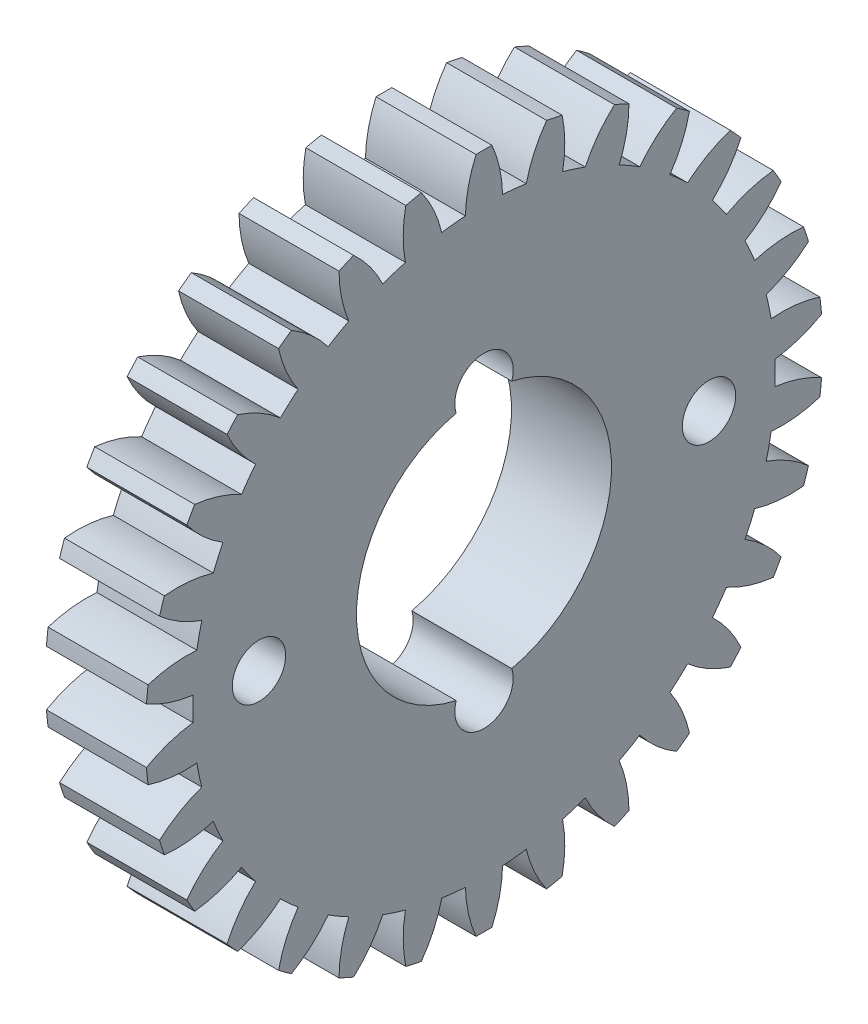
SolidWorks part; units mm, degrees
material "Aço 4140"
ref_plane "Plano frontal" through (0, 0, 0) normal (0, 0, 1) x (1, 0, 0)
ref_plane "Plano superior" through (0, 0, 0) normal (0, 1, 0) x (1, 0, 0)
ref_plane "Plano direito" through (0, 0, 0) normal (1, 0, 0) x (0, 0, -1)
ref_plane "Plano1" through (0, 0, 0) normal (-1, 0, 0) x (0, -1, 0)
sketch "Esboço1" plane through (0, 0, 0) normal (-1, 0, 0) x (0, -1, 0)
  circle A0 centre (8, 0) radius 1.75
  circle A1 centre (0, 0) radius 3
  circle A2 centre (-8, 0) radius 1.75
  arc A3 (17.4396, -1.1143) -> (20.3144, -0.4769) centre (17.2585, 6.5035) ccw
  arc A4 (20.3144, -0.4769) -> (20.3144, 0.4769) centre (0, 0) ccw
  arc A5 (20.3144, 0.4769) -> (17.4396, 1.1143) centre (17.2585, -6.5035) ccw
  arc A6 (17.4396, 1.1143) -> (17.2902, 2.5359) centre (0, 0) ccw
  arc A7 (17.2902, 2.5359) -> (19.9696, 3.7571) centre (15.5292, 9.9496) ccw
  arc A8 (19.9696, 3.7571) -> (19.7713, 4.6901) centre (0, 0) ccw
  arc A9 (19.7713, 4.6901) -> (16.8269, 4.7159) centre (18.2335, -2.7732) ccw
  arc A10 (16.8269, 4.7159) -> (16.3851, 6.0754) centre (0, 0) ccw
  arc A11 (16.3851, 6.0754) -> (18.7521, 7.827) centre (13.1212, 12.9609) ccw
  arc A12 (18.7521, 7.827) -> (18.3642, 8.6983) centre (0, 0) ccw
  arc A13 (18.3642, 8.6983) -> (15.4787, 8.1113) centre (18.4117, 1.0784) ccw
  arc A14 (15.4787, 8.1113) -> (14.7639, 9.3493) centre (0, 0) ccw
  arc A15 (14.7639, 9.3493) -> (16.715, 11.5547) centre (10.1398, 15.4058) ccw
  arc A16 (16.715, 11.5547) -> (16.1544, 12.3263) centre (0, 0) ccw
  arc A17 (16.1544, 12.3263) -> (13.454, 11.1523) centre (17.7851, 4.8828) ccw
  arc A18 (13.454, 11.1523) -> (12.4975, 12.2145) centre (0, 0) ccw
  arc A19 (12.4975, 12.2145) -> (13.9474, 14.7775) centre (6.7151, 17.1773) ccw
  arc A20 (13.9474, 14.7775) -> (13.2386, 15.4156) centre (0, 0) ccw
  arc A21 (13.2386, 15.4156) -> (10.8413, 13.7058) centre (16.3813, 8.4739) ccw
  arc A22 (10.8413, 13.7058) -> (9.6849, 14.546) centre (0, 0) ccw
  arc A23 (9.6849, 14.546) -> (10.5702, 17.3544) centre (2.997, 18.1981) ccw
  arc A24 (10.5702, 17.3544) -> (9.7442, 17.8312) centre (0, 0) ccw
  arc A25 (9.7442, 17.8312) -> (7.7548, 15.6603) centre (14.2615, 11.6946) ccw
  arc A26 (7.7548, 15.6603) -> (6.4489, 16.2417) centre (0, 0) ccw
  arc A27 (6.4489, 16.2417) -> (6.731, 19.1728) centre (-0.852, 18.4235) ccw
  arc A28 (6.731, 19.1728) -> (5.824, 19.4675) centre (0, 0) ccw
  arc A29 (5.824, 19.4675) -> (4.3294, 16.9304) centre (11.5184, 14.4041) ccw
  arc A30 (4.3294, 16.9304) -> (2.9312, 17.2276) centre (0, 0) ccw
  arc A31 (2.9312, 17.2276) -> (2.5977, 20.1533) centre (-4.6639, 17.8438) ccw
  arc A32 (2.5977, 20.1533) -> (1.6492, 20.253) centre (0, 0) ccw
  arc A33 (1.6492, 20.253) -> (0.7147, 17.4606) centre (8.2719, 16.4842) ccw
  arc A34 (0.7147, 17.4606) -> (-0.7147, 17.4606) centre (0, 0) ccw
  arc A35 (-0.7147, 17.4606) -> (-1.6492, 20.253) centre (-8.2719, 16.4842) ccw
  arc A36 (-1.6492, 20.253) -> (-2.5977, 20.1533) centre (0, 0) ccw
  arc A37 (-2.5977, 20.1533) -> (-2.9312, 17.2276) centre (4.6639, 17.8438) ccw
  arc A38 (-2.9312, 17.2276) -> (-4.3294, 16.9304) centre (0, 0) ccw
  arc A39 (-4.3294, 16.9304) -> (-5.824, 19.4675) centre (-11.5184, 14.4041) ccw
  arc A40 (-5.824, 19.4675) -> (-6.731, 19.1728) centre (0, 0) ccw
  arc A41 (-6.731, 19.1728) -> (-6.4489, 16.2417) centre (0.852, 18.4235) ccw
  arc A42 (-6.4489, 16.2417) -> (-7.7548, 15.6603) centre (0, 0) ccw
  arc A43 (-7.7548, 15.6603) -> (-9.7442, 17.8312) centre (-14.2615, 11.6946) ccw
  arc A44 (-9.7442, 17.8312) -> (-10.5702, 17.3544) centre (0, 0) ccw
  arc A45 (-10.5702, 17.3544) -> (-9.6849, 14.546) centre (-2.997, 18.1981) ccw
  arc A46 (-9.6849, 14.546) -> (-10.8413, 13.7058) centre (0, 0) ccw
  arc A47 (-10.8413, 13.7058) -> (-13.2386, 15.4156) centre (-16.3813, 8.4739) ccw
  arc A48 (-13.2386, 15.4156) -> (-13.9474, 14.7775) centre (0, 0) ccw
  arc A49 (-13.9474, 14.7775) -> (-12.4975, 12.2145) centre (-6.7151, 17.1773) ccw
  arc A50 (-12.4975, 12.2145) -> (-13.454, 11.1523) centre (0, 0) ccw
  arc A51 (-13.454, 11.1523) -> (-16.1544, 12.3263) centre (-17.7851, 4.8828) ccw
  arc A52 (-16.1544, 12.3263) -> (-16.715, 11.5547) centre (0, 0) ccw
  arc A53 (-16.715, 11.5547) -> (-14.7639, 9.3493) centre (-10.1398, 15.4058) ccw
  arc A54 (-14.7639, 9.3493) -> (-15.4787, 8.1113) centre (0, 0) ccw
  arc A55 (-15.4787, 8.1113) -> (-18.3642, 8.6983) centre (-18.4117, 1.0784) ccw
  arc A56 (-18.3642, 8.6983) -> (-18.7521, 7.827) centre (0, 0) ccw
  arc A57 (-18.7521, 7.827) -> (-16.3851, 6.0754) centre (-13.1212, 12.9609) ccw
  arc A58 (-16.3851, 6.0754) -> (-16.8269, 4.7159) centre (0, 0) ccw
  arc A59 (-16.8269, 4.7159) -> (-19.7713, 4.6901) centre (-18.2335, -2.7732) ccw
  arc A60 (-19.7713, 4.6901) -> (-19.9696, 3.7571) centre (0, 0) ccw
  arc A61 (-19.9696, 3.7571) -> (-17.2902, 2.5359) centre (-15.5292, 9.9496) ccw
  arc A62 (-17.2902, 2.5359) -> (-17.4396, 1.1143) centre (0, 0) ccw
  arc A63 (-17.4396, 1.1143) -> (-20.3144, 0.4769) centre (-17.2585, -6.5035) ccw
  arc A64 (-20.3144, 0.4769) -> (-20.3144, -0.4769) centre (0, 0) ccw
  arc A65 (-20.3144, -0.4769) -> (-17.4396, -1.1143) centre (-17.2585, 6.5035) ccw
  arc A66 (-17.4396, -1.1143) -> (-17.2902, -2.5359) centre (0, 0) ccw
  arc A67 (-17.2902, -2.5359) -> (-19.9696, -3.7571) centre (-15.5292, -9.9496) ccw
  arc A68 (-19.9696, -3.7571) -> (-19.7713, -4.6901) centre (0, 0) ccw
  arc A69 (-19.7713, -4.6901) -> (-16.8269, -4.7159) centre (-18.2335, 2.7732) ccw
  arc A70 (-16.8269, -4.7159) -> (-16.3851, -6.0754) centre (0, 0) ccw
  arc A71 (-16.3851, -6.0754) -> (-18.7521, -7.827) centre (-13.1212, -12.9609) ccw
  arc A72 (-18.7521, -7.827) -> (-18.3642, -8.6983) centre (0, 0) ccw
  arc A73 (-18.3642, -8.6983) -> (-15.4787, -8.1113) centre (-18.4117, -1.0784) ccw
  arc A74 (-15.4787, -8.1113) -> (-14.7639, -9.3493) centre (0, 0) ccw
  arc A75 (-14.7639, -9.3493) -> (-16.715, -11.5547) centre (-10.1398, -15.4058) ccw
  arc A76 (-16.715, -11.5547) -> (-16.1544, -12.3263) centre (0, 0) ccw
  arc A77 (-16.1544, -12.3263) -> (-13.454, -11.1523) centre (-17.7851, -4.8828) ccw
  arc A78 (-13.454, -11.1523) -> (-12.4975, -12.2145) centre (0, 0) ccw
  arc A79 (-12.4975, -12.2145) -> (-13.9474, -14.7775) centre (-6.7151, -17.1773) ccw
  arc A80 (-13.9474, -14.7775) -> (-13.2386, -15.4156) centre (0, 0) ccw
  arc A81 (-13.2386, -15.4156) -> (-10.8413, -13.7058) centre (-16.3813, -8.4739) ccw
  arc A82 (-10.8413, -13.7058) -> (-9.6849, -14.546) centre (0, 0) ccw
  arc A83 (-9.6849, -14.546) -> (-10.5702, -17.3544) centre (-2.997, -18.1981) ccw
  arc A84 (-10.5702, -17.3544) -> (-9.7442, -17.8312) centre (0, 0) ccw
  arc A85 (-9.7442, -17.8312) -> (-7.7548, -15.6603) centre (-14.2615, -11.6946) ccw
  arc A86 (-7.7548, -15.6603) -> (-6.4489, -16.2417) centre (0, 0) ccw
  arc A87 (-6.4489, -16.2417) -> (-6.731, -19.1728) centre (0.852, -18.4235) ccw
  arc A88 (-6.731, -19.1728) -> (-5.824, -19.4675) centre (0, 0) ccw
  arc A89 (-5.824, -19.4675) -> (-4.3294, -16.9304) centre (-11.5184, -14.4041) ccw
  arc A90 (-4.3294, -16.9304) -> (-2.9312, -17.2276) centre (0, 0) ccw
  arc A91 (-2.9312, -17.2276) -> (-2.5977, -20.1533) centre (4.6639, -17.8438) ccw
  arc A92 (-2.5977, -20.1533) -> (-1.6492, -20.253) centre (0, 0) ccw
  arc A93 (-1.6492, -20.253) -> (-0.7147, -17.4606) centre (-8.2719, -16.4842) ccw
  arc A94 (-0.7147, -17.4606) -> (0.7147, -17.4606) centre (0, 0) ccw
  arc A95 (0.7147, -17.4606) -> (1.6492, -20.253) centre (8.2719, -16.4842) ccw
  arc A96 (1.6492, -20.253) -> (2.5977, -20.1533) centre (0, 0) ccw
  arc A97 (2.5977, -20.1533) -> (2.9312, -17.2276) centre (-4.6639, -17.8438) ccw
  arc A98 (2.9312, -17.2276) -> (4.3294, -16.9304) centre (0, 0) ccw
  arc A99 (4.3294, -16.9304) -> (5.824, -19.4675) centre (11.5184, -14.4041) ccw
  arc A100 (5.824, -19.4675) -> (6.731, -19.1728) centre (0, 0) ccw
  arc A101 (6.731, -19.1728) -> (6.4489, -16.2417) centre (-0.852, -18.4235) ccw
  arc A102 (6.4489, -16.2417) -> (7.7548, -15.6603) centre (0, 0) ccw
  arc A103 (7.7548, -15.6603) -> (9.7442, -17.8312) centre (14.2615, -11.6946) ccw
  arc A104 (9.7442, -17.8312) -> (10.5702, -17.3544) centre (0, 0) ccw
  arc A105 (10.5702, -17.3544) -> (9.6849, -14.546) centre (2.997, -18.1981) ccw
  arc A106 (9.6849, -14.546) -> (10.8413, -13.7058) centre (0, 0) ccw
  arc A107 (10.8413, -13.7058) -> (13.2386, -15.4156) centre (16.3813, -8.4739) ccw
  arc A108 (13.2386, -15.4156) -> (13.9474, -14.7775) centre (0, 0) ccw
  arc A109 (13.9474, -14.7775) -> (12.4975, -12.2145) centre (6.7151, -17.1773) ccw
  arc A110 (12.4975, -12.2145) -> (13.454, -11.1523) centre (0, 0) ccw
  arc A111 (13.454, -11.1523) -> (16.1544, -12.3263) centre (17.7851, -4.8828) ccw
  arc A112 (16.1544, -12.3263) -> (16.715, -11.5547) centre (0, 0) ccw
  arc A113 (16.715, -11.5547) -> (14.7639, -9.3493) centre (10.1398, -15.4058) ccw
  arc A114 (14.7639, -9.3493) -> (15.4787, -8.1113) centre (0, 0) ccw
  arc A115 (15.4787, -8.1113) -> (18.3642, -8.6983) centre (18.4117, -1.0784) ccw
  arc A116 (18.3642, -8.6983) -> (18.7521, -7.827) centre (0, 0) ccw
  arc A117 (18.7521, -7.827) -> (16.3851, -6.0754) centre (13.1212, -12.9609) ccw
  arc A118 (16.3851, -6.0754) -> (16.8269, -4.7159) centre (0, 0) ccw
  arc A119 (16.8269, -4.7159) -> (19.7713, -4.6901) centre (18.2335, 2.7732) ccw
  arc A120 (19.7713, -4.6901) -> (19.9696, -3.7571) centre (0, 0) ccw
  arc A121 (19.9696, -3.7571) -> (17.2902, -2.5359) centre (15.5292, -9.9496) ccw
  arc A122 (17.2902, -2.5359) -> (17.4396, -1.1143) centre (0, 0) ccw
extrude "Ressalto-extrusão1" add sketch "Esboço1" against normal blind 6
sketch "Esboço2" plane through (6, 0, 0) normal (1, 0, 0) x (0, 0, -1)
  line L0 (-13.5, 0) -> (13.5, 0) construction
  circle A0 centre (-13.5, 0) radius 1.6
  circle A1 centre (13.5, 0) radius 1.6
  circle A2 centre (0, 0) radius 7.65
  dimension "D1" = 15.3
  dimension "D2" = 3.2
  dimension "D3" = 27
extrude "Corte-extrusão1" cut sketch "Esboço2" against normal through all both
